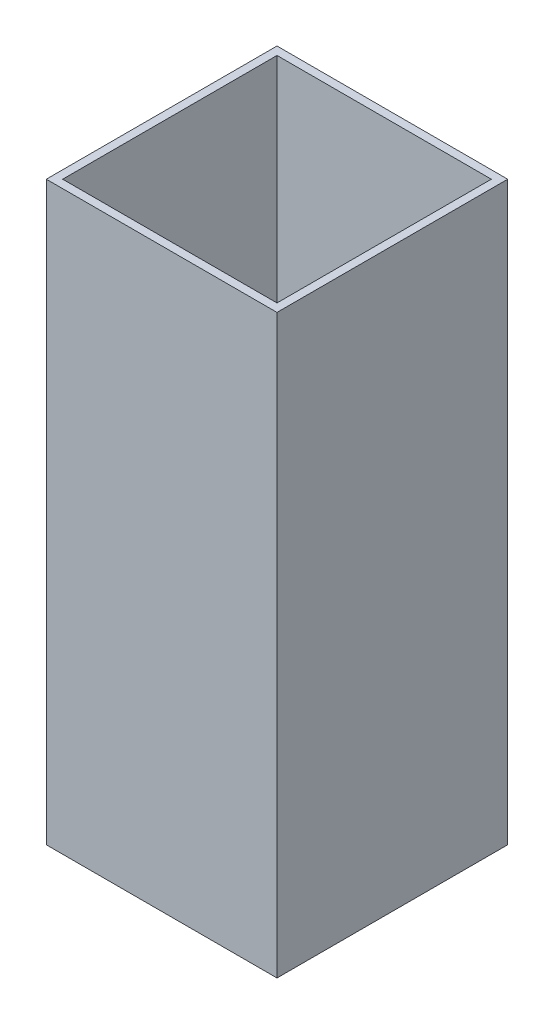
SolidWorks part; units mm, degrees
ref_plane "Front Plane" through (0, 0, 0) normal (0, 0, 1) x (1, 0, 0)
ref_plane "Top Plane" through (0, 0, 0) normal (0, 1, 0) x (1, 0, 0)
ref_plane "Right Plane" through (0, 0, 0) normal (1, 0, 0) x (0, 0, -1)
sketch "Sketch1" plane through (0, 0, 0) normal (0, 1, 0) x (1, 0, 0)
  line L1 (-50.75, 50.75) -> (50.75, 50.75)
  line L2 (-50.75, 50.75) -> (-50.75, -50.75)
  line L3 (-50.75, -50.75) -> (50.75, -50.75)
  line L4 (50.75, 50.75) -> (50.75, -50.75)
  line L5 (-50.75, 50.75) -> (50.75, -50.75) construction
  line L6 (-50.75, -50.75) -> (50.75, 50.75) construction
  point P0 (0, 0)
  dimension "D1" = 101.5
  dimension "D2" = 101.5
extrude "Boss-Extrude1" add sketch "Sketch1" along normal blind 3.6
sketch "Sketch2" plane through (0, 3.6, 0) normal (0, 1, 0) x (1, 0, 0)
  line L0 (47.15, -47.15) -> (47.15, 47.15)
  line L1 (47.15, 47.15) -> (-47.15, 47.15)
  line L2 (-47.15, 47.15) -> (-47.15, -47.15)
  line L3 (-47.15, -47.15) -> (47.15, -47.15)
  line L4 (50.75, -50.75) -> (50.75, 50.75)
  line L5 (50.75, 50.75) -> (-50.75, 50.75)
  line L6 (-50.75, 50.75) -> (-50.75, -50.75)
  line L7 (-50.75, -50.75) -> (50.75, -50.75)
  line L8 (50.75, -50.75) -> (50.75, 50.75)
  line L9 (50.75, 50.75) -> (-50.75, 50.75)
  line L10 (-50.75, 50.75) -> (-50.75, -50.75)
  line L11 (-50.75, -50.75) -> (50.75, -50.75)
  dimension "D1" = 0
  dimension "D2" = 3.6
extrude "Boss-Extrude2" add sketch "Sketch2" along normal blind 250
